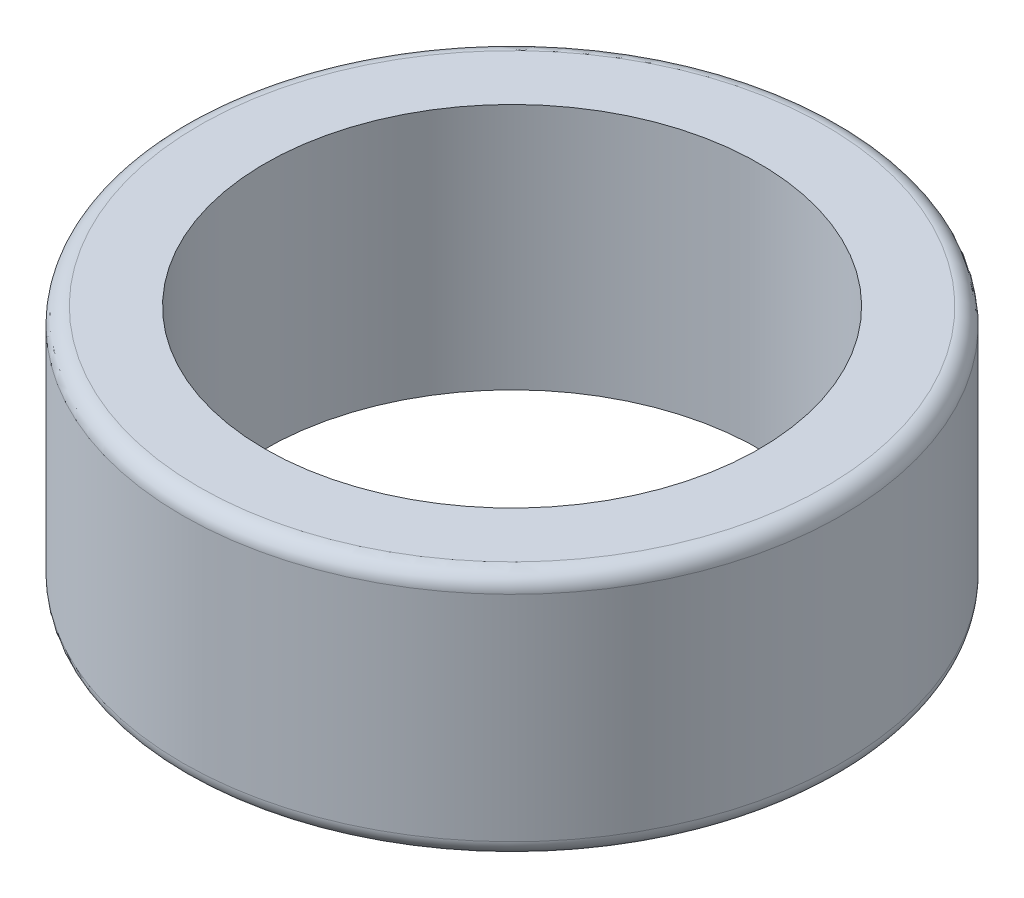
SolidWorks part; units mm, degrees
ref_plane "Ebene vorne" through (0, 0, 0) normal (0, 0, 1) x (1, 0, 0)
ref_plane "Ebene oben" through (0, 0, 0) normal (0, 1, 0) x (1, 0, 0)
ref_plane "Ebene rechts" through (0, 0, 0) normal (1, 0, 0) x (0, 0, -1)
sketch "Skizze1" plane through (0, 0, 0) normal (0, 1, 0) x (1, 0, 0)
  circle A0 centre (0, 0) radius 3
  circle A1 centre (0, 0) radius 4
  dimension "D1" = 6
  dimension "D2" = 1
extrude "Aufsatz-Linear austragen1" add sketch "Skizze1" along normal blind 3
fillet "Verrundung1" radius 0.2 2 edges at (0, 0, 4) (0, 3, 4)
